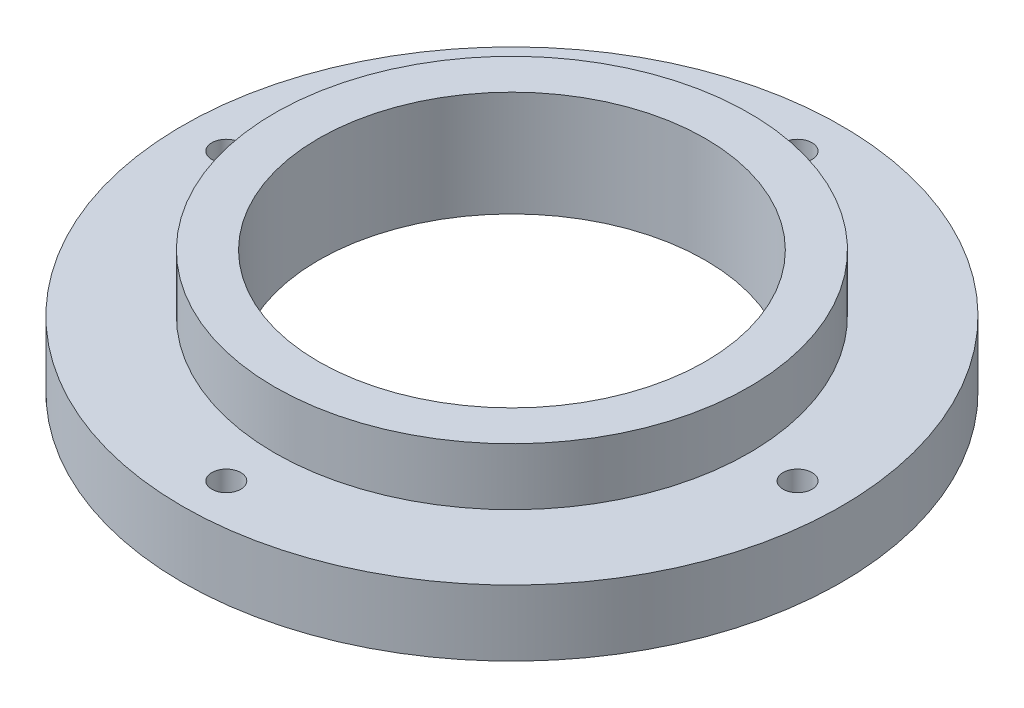
SolidWorks part; units mm, degrees
material "1.7218 (25CrMo4)"
ref_plane "Ebene vorne" through (0, 0, 0) normal (0, 0, 1) x (1, 0, 0)
ref_plane "Ebene oben" through (0, 0, 0) normal (0, 1, 0) x (1, 0, 0)
ref_plane "Ebene rechts" through (0, 0, 0) normal (1, 0, 0) x (0, 0, -1)
sketch "Skizze1" plane through (0, 0, 0) normal (0, 1, 0) x (1, 0, 0)
  circle A0 centre (0, 0) radius 22
  circle A1 centre (0, 0) radius 37.5
  dimension "D1" = 44
  dimension "D2" = 75
extrude "Aufsatz-Linear austragen1" add sketch "Skizze1" along normal blind 14
sketch "Skizze2" plane through (0, 14, 0) normal (0, 1, 0) x (1, 0, 0)
  circle A0 centre (0, 0) radius 37.5
  circle A1 centre (0, 0) radius 37.5 construction
  circle A2 centre (0, 0) radius 27
  circle A4 centre (0, 0) radius 22 construction
  dimension "D1" = 5
extrude "Schnitt-Linear austragen1" cut sketch "Skizze2" against normal blind 6.5
hole_wizard "M4x0.7 Gewindebohrung1" positions "Skizze3" profile "Skizze4" tap size "M4x0.7" standard "ANSI Metrisch" end condition up to next
sketch "Skizze3" plane through (0, 7.5, 0) normal (0, 1, 0) x (1, 0, 0)
  line L0 (-37.5, 0) -> (37.5, 0) construction
  line L2 (0, -37.5) -> (0, 37.5) construction
  circle A0 centre (0, 0) radius 37.5 construction
  circle A1 centre (0, 0) radius 32.5 construction
  point P0 (-32.5, 0)
  point P18 (0, 32.5)
  point P20 (0, -32.5)
  point P22 (32.5, 0)
  dimension "D1" = 65
sketch "Skizze4" plane through (-32.5, 7.5, 0) normal (1, 0, 0) x (0, 0, 1)
  line L0 (0, 0) -> (0, 7.5)
  line L1 (0, 7.5) -> (1.65, 7.5)
  line L2 (1.65, 7.5) -> (1.65, 0)
  line L5 (1.65, 0) -> (0, 0)
  line L11 (0, -6.35) -> (0, 107.95) construction
  dimension "Bohrerdurchmesser" = 3.3
  dimension "Bohrungstiefe" = 7.5
cosmetic thread "Bohrungsgewinde1" parameters "D2"=4
cosmetic thread "Bohrungsgewinde2" parameters "D2"=4
cosmetic thread "Bohrungsgewinde3" parameters "D2"=4
cosmetic thread "Bohrungsgewinde4" parameters "D2"=4
sketch "Skizze5" plane through (0, 0, 0) normal (0, -1, 0) x (1, 0, 0)
  circle A0 centre (0, 0) radius 26.5
  dimension "D1" = 53
extrude "Schnitt-Linear austragen2" cut sketch "Skizze5" against normal blind 2
